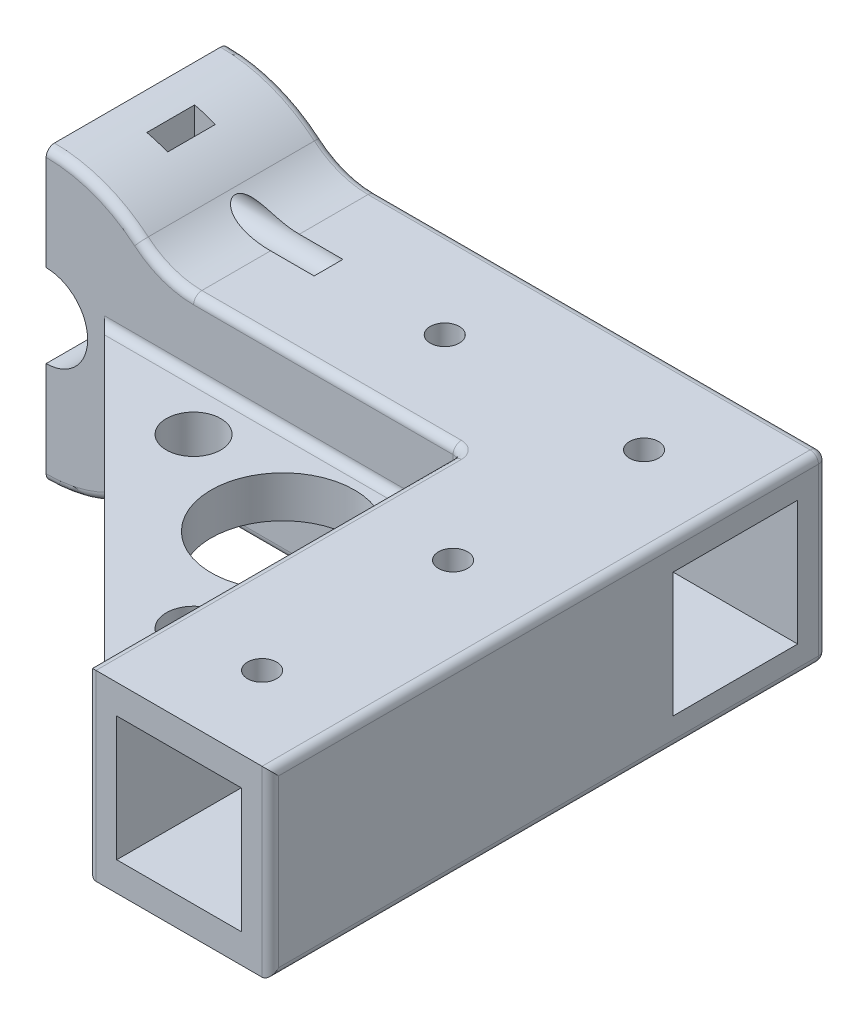
SolidWorks part; units mm, degrees
ref_plane "Front Plane" through (0, 0, 0) normal (0, 0, 1) x (1, 0, 0)
ref_plane "Top Plane" through (0, 0, 0) normal (0, 1, 0) x (1, 0, 0)
ref_plane "Right Plane" through (0, 0, 0) normal (1, 0, 0) x (0, 0, -1)
sketch "Sketch1" plane through (0, 0, 0) normal (0, 0, 1) x (1, 0, 0)
  line L0 (41.5599, 4.1233) -> (41.5599, -17.8767) construction
  line L1 (5.1706, 4.1233) -> (63.5599, 4.1233)
  line L2 (-8.4401, 7.6443) -> (-8.4401, -1.8767)
  line L3 (5.1706, -17.8767) -> (63.5599, -17.8767)
  line L4 (63.5599, 4.1233) -> (63.5599, -17.8767)
  line L5 (-8.4401, -11.8767) -> (-8.4401, -14.3557)
  line L6 (-8.4401, -14.3557) -> (-8.4401, -24.3767)
  line L7 (-8.4401, 7.6443) -> (-8.4401, 10.6233)
  arc A0 (-8.4401, -11.8767) -> (-8.4401, -1.8767) centre (-8.4401, -6.8767) ccw
  arc A1 (5.1706, 4.1233) -> (-8.4401, 10.6233) centre (-8.4401, -6.8767) ccw
  arc A2 (-8.4401, -24.3767) -> (5.1706, -17.8767) centre (-8.4401, -6.8767) ccw
  dimension "D4" = 10
  dimension "D5" = 35
  dimension "D1" = 22
  dimension "D2" = 50
  dimension "D3" = 22
  dimension "D6" = 11
extrude "Boss-Extrude1" add sketch "Sketch1" along normal blind 22
sketch "Sketch2" plane through (0, 0, 22) normal (0, 0, 1) x (1, 0, 0)
  line L0 (5.1706, -17.8767) -> (63.5599, -17.8767) construction
  line L1 (63.5599, 4.1233) -> (41.5599, 4.1233)
  line L2 (63.5599, 4.1233) -> (63.5599, -17.8767)
  line L3 (63.5599, -17.8767) -> (41.5599, -17.8767)
  line L4 (41.5599, 4.1233) -> (41.5599, -17.8767)
  dimension "D1" = 22
extrude "Boss-Extrude2" add sketch "Sketch2" along normal blind 45
sketch "Sketch3" plane through (0, 0, 67) normal (0, 0, 1) x (1, 0, 0)
  line L0 (63.5599, -17.8767) -> (63.5599, 4.1233) construction
  line L1 (45.0599, 0.6233) -> (60.0599, 0.6233)
  line L2 (45.0599, 0.6233) -> (45.0599, -14.3767)
  line L3 (45.0599, -14.3767) -> (60.0599, -14.3767)
  line L4 (60.0599, 0.6233) -> (60.0599, -14.3767)
  line L5 (63.5599, 4.1233) -> (41.5599, 4.1233) construction
  dimension "D1" = 15
  dimension "D2" = 3.5
  dimension "D3" = 15
  dimension "D4" = 3.5
extrude "Cut-Extrude1" cut sketch "Sketch3" against normal offset from surface (43 mm away) 2 up to face at (8.2716, -5.5017, 22)
sketch "Sketch4" plane through (63.5599, 0, 0) normal (1, 0, 0) x (0, 0, -1)
  line L0 (-67, 4.1233) -> (0, 4.1233) construction
  line L1 (-3.5, 0.6233) -> (-18.5, 0.6233)
  line L2 (-3.5, 0.6233) -> (-3.5, -14.3767)
  line L3 (-3.5, -14.3767) -> (-18.5, -14.3767)
  line L4 (-18.5, 0.6233) -> (-18.5, -14.3767)
  line L5 (0, -17.8767) -> (0, 4.1233) construction
  dimension "D1" = 15
  dimension "D2" = 15
  dimension "D3" = 3.5
  dimension "D4" = 3.5
extrude "Cut-Extrude2" cut sketch "Sketch4" against normal blind 45
ref_plane "Plane1" through (0, -6.8767, 0) normal (0, 1, 0) x (1, 0, 0)
sketch "Sketch6" plane through (0, -6.8767, 0) normal (0, 1, 0) x (1, 0, 0)
  line L0 (-1.4401, -22) -> (41.5599, -65)
  line L1 (41.5599, -22) -> (5.1706, -22) construction
  line L2 (41.5599, -67) -> (41.5599, -22) construction
  line L3 (41.5599, -65) -> (41.5599, -22)
  line L4 (41.5599, -22) -> (-1.4401, -22)
  line L5 (-3.4401, -22) -> (-3.4401, 0) construction
  dimension "D1" = 2
  dimension "D2" = 45
extrude "Boss-Extrude3" add sketch "Sketch6" along normal blind 2.5 and the other way blind 2.5
fillet "Fillet1" radius 10 2 edges at (5.1706, -17.8767, 11) (5.1706, 4.1233, 11)
sketch "Sketch5" plane through (-8.4401, 0, 0) normal (-1, 0, 0) x (0, 0, 1)
  line L0 (0, 4.3733) -> (22, 4.3733) construction
  line L1 (0, 10.6233) -> (0, -1.8767) construction
  line L2 (22, 10.6233) -> (22, -1.8767) construction
  line L3 (0, -18.1267) -> (22, -18.1267) construction
  line L4 (0, -11.8767) -> (0, -24.3767) construction
  line L5 (22, -11.8767) -> (22, -24.3767) construction
  circle A1 centre (11, 4.3733) radius 1.75
  circle A3 centre (11, -18.1267) radius 1.75
  dimension "D1" = 3.5
  dimension "D4" = 11
  dimension "D5" = 11
extrude "Cut-Extrude3" cut sketch "Sketch5" against normal blind 23
sketch "Sketch7" plane through (0, 4.1233, 0) normal (0, 1, 0) x (1, 0, 0)
  line L1 (14.5599, -9.2679) -> (14.5599, -12.7321) construction
  line L2 (-4.4401, -8.125) -> (-1.9401, -8.125)
  line L3 (-4.4401, -8.125) -> (-4.4401, -13.875)
  line L4 (-4.4401, -13.875) -> (-1.9401, -13.875)
  line L5 (-1.9401, -8.125) -> (-1.9401, -13.875)
  line L7 (-8.4401, -22) -> (-8.4401, 0) construction
  point P0 (14.5599, -11)
  dimension "D1" = 5.75
  dimension "D2" = 2.875
  dimension "D3" = 4
  dimension "D4" = 2.5
extrude "Cut-Extrude4" cut sketch "Sketch7" against normal blind 3.5 and the other way blind 10
mirror "Mirror1" about plane through (0, -6.8767, 0) normal (0, 1, 0) of "Cut-Extrude4"
sketch "Sketch8" plane through (0, -17.8767, 0) normal (0, -1, 0) x (1, 0, 0)
  line L0 (18.5599, 11) -> (63.5599, 11) construction
  line L1 (18.5599, 18.5) -> (18.5599, 3.5) construction
  line L2 (63.5599, 67) -> (63.5599, 0) construction
  line L3 (52.5599, 24) -> (52.5599, 67) construction
  line L4 (60.0599, 24) -> (45.0599, 24) construction
  line L5 (41.5599, 67) -> (63.5599, 67) construction
  circle A0 centre (28.5599, 11) radius 1.75
  circle A1 centre (52.5599, 11) radius 1.75
  circle A2 centre (52.5599, 34) radius 1.75
  circle A3 centre (52.5599, 57) radius 1.75
  dimension "D1" = 3.5
  dimension "D2" = 10
  dimension "D3" = 10
  dimension "D4" = 10
extrude "Cut-Extrude5" cut sketch "Sketch8" against normal up to surface (22 mm away)
sketch "Sketch9" plane through (0, 0, 0) normal (0, 0, -1) x (-1, 0, 0)
  line L0 (-61.5599, -12.8767) -> (-9.3152, -12.8767) construction
  line L2 (-9.3152, -17.8767) -> (-63.5599, -17.8767) construction
  line L3 (-63.5599, -17.8767) -> (-63.5599, 4.1233) construction
  text T0 "ALFR3D" font "Murder Of Mayday" height 12
  dimension "D1" = 5
  dimension "D2" = 2
extrude "Cut-Extrude6" cut sketch "Sketch9" against normal blind 1.5
sketch "Sketch10" plane through (0, -9.3767, 0) normal (0, -1, 0) x (1, 0, 0)
  line L0 (41.5599, 22) -> (20.0599, 43.5) construction
  line L1 (-1.4401, 22) -> (41.5599, 65) construction
  line L2 (41.5599, 67) -> (41.5599, 22) construction
  line L3 (41.5599, 22) -> (-1.4401, 22) construction
  circle A0 centre (30.8099, 32.75) radius 8.6369
  circle A1 centre (35.5599, 48.25) radius 3.2807
  circle A2 centre (15.3099, 28) radius 3.2807
  dimension "D1" = 6
  dimension "D2" = 6
  dimension "D3" = 15.5
  dimension "D4" = 15.5
extrude "Cut-Extrude7" cut sketch "Sketch10" against normal up to surface (5 mm away) up to face at (27.2266, -4.3767, 36.3333)
fillet "Fillet2" radius 1 25 edges at (-2.424, 9.5567, 22) (5.8774, 4.7328, 22) (-2.424, -23.3101, 22) (5.8774, -18.4862, 22) (-2.424, -23.3101, 0) (5.8774, -18.4862, 0) (-2.424, 9.5567, 0) (5.8774, 4.7328, 0) (41.5599, -6.8767, 67) (63.5599, -6.8767, 67) (20.0599, -9.3767, 22) (41.5599, -9.3767, 43.5) (20.0599, -4.3767, 22) (41.5599, -4.3767, 43.5) (63.5599, 4.1233, 33.5) (63.5599, -17.8767, 33.5) (63.5599, -6.8767, 0) (36.4376, -17.8767, 0) (36.4376, 4.1233, 0)
